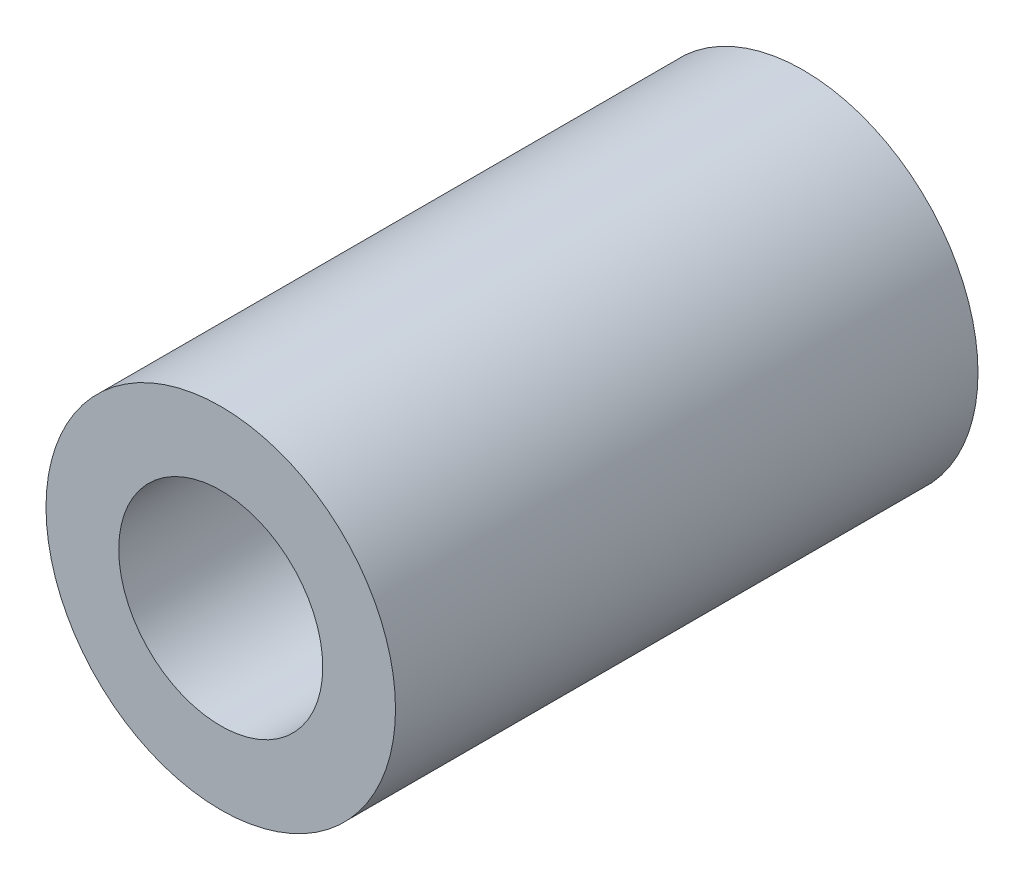
SolidWorks part; units mm, degrees
ref_plane "Front Plane" through (0, 0, 0) normal (0, 0, 1) x (1, 0, 0)
ref_plane "Top Plane" through (0, 0, 0) normal (0, 1, 0) x (1, 0, 0)
ref_plane "Right Plane" through (0, 0, 0) normal (1, 0, 0) x (0, 0, -1)
sketch "Sketch1" plane through (0, 0, 0) normal (0, 0, 1) x (1, 0, 0)
  circle A0 centre (0, 0) radius 2.78
  circle A1 centre (0, 0) radius 4.7625
  dimension "D1" = 5.56
  dimension "D2" = 9.525
extrude "Boss-Extrude1" add sketch "Sketch1" along normal blind 15.875
